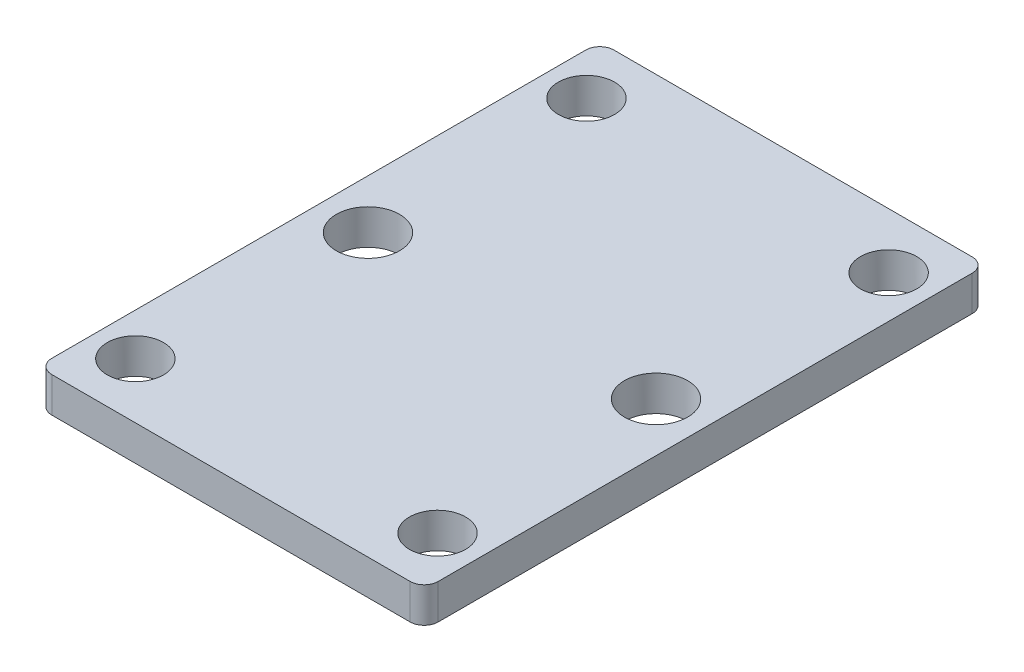
SolidWorks part; units mm, degrees
ref_plane "Alzado" through (0, 0, 0) normal (0, 0, 1) x (1, 0, 0)
ref_plane "Planta" through (0, 0, 0) normal (0, 1, 0) x (1, 0, 0)
ref_plane "Vista lateral" through (0, 0, 0) normal (1, 0, 0) x (0, 0, -1)
sketch "Croquis1" plane through (0, 0, 0) normal (0, 1, 0) x (1, 0, 0)
  line L0 (-27.5, 0) -> (27.5, 0) construction
  line L2 (-27.5, -38) -> (-27.5, 38)
  line L3 (-25.5, 40) -> (25.5, 40)
  line L4 (27.5, 38) -> (27.5, -38)
  line L5 (0, 40) -> (0, -40) construction
  line L7 (-25.5, -40) -> (25.5, -40)
  arc A0 (25.5, -40) -> (27.5, -38) centre (25.5, -38) ccw
  arc A1 (25.5, 40) -> (27.5, 38) centre (25.5, 38) cw
  arc A2 (-25.5, -40) -> (-27.5, -38) centre (-25.5, -38) cw
  arc A3 (-27.5, 38) -> (-25.5, 40) centre (-25.5, 38) cw
  point P11 (27.5, -40)
  point P16 (-27.5, -40)
  point P19 (-27.5, 40)
  dimension "D3" = 2
  dimension "D1" = 55
  dimension "D2" = 80
extrude "Saliente-Extruir1" add sketch "Croquis1" along normal blind 5
sketch "Croquis2" plane through (0, 5, 0) normal (0, 1, 0) x (1, 0, 0)
  line L0 (-27.5, 0) -> (27.5, 0) construction
  line L1 (-27.5, 38) -> (-27.5, -38) construction
  line L3 (0, -40) -> (0, 40) construction
  line L4 (-25.5, -40) -> (25.5, -40) construction
  line L5 (25.5, 40) -> (-25.5, 40) construction
  line L6 (27.5, -38) -> (27.5, 38) construction
  circle A0 centre (-20.5, 0) radius 4.5
  circle A1 centre (20.5, 0) radius 4.5
  circle A4 centre (-21.5, 32.1) radius 4
  circle A5 centre (-21.5, -32.1) radius 4
  circle A6 centre (21.5, 32.1) radius 4
  circle A7 centre (21.5, -32.1) radius 4
  dimension "D2" = 9
  dimension "D5" = 8
  dimension "D1" = 7
  dimension "D4" = 6
  dimension "D6" = 64.2
extrude "Cortar-Extruir1" cut sketch "Croquis2" against normal blind 10
